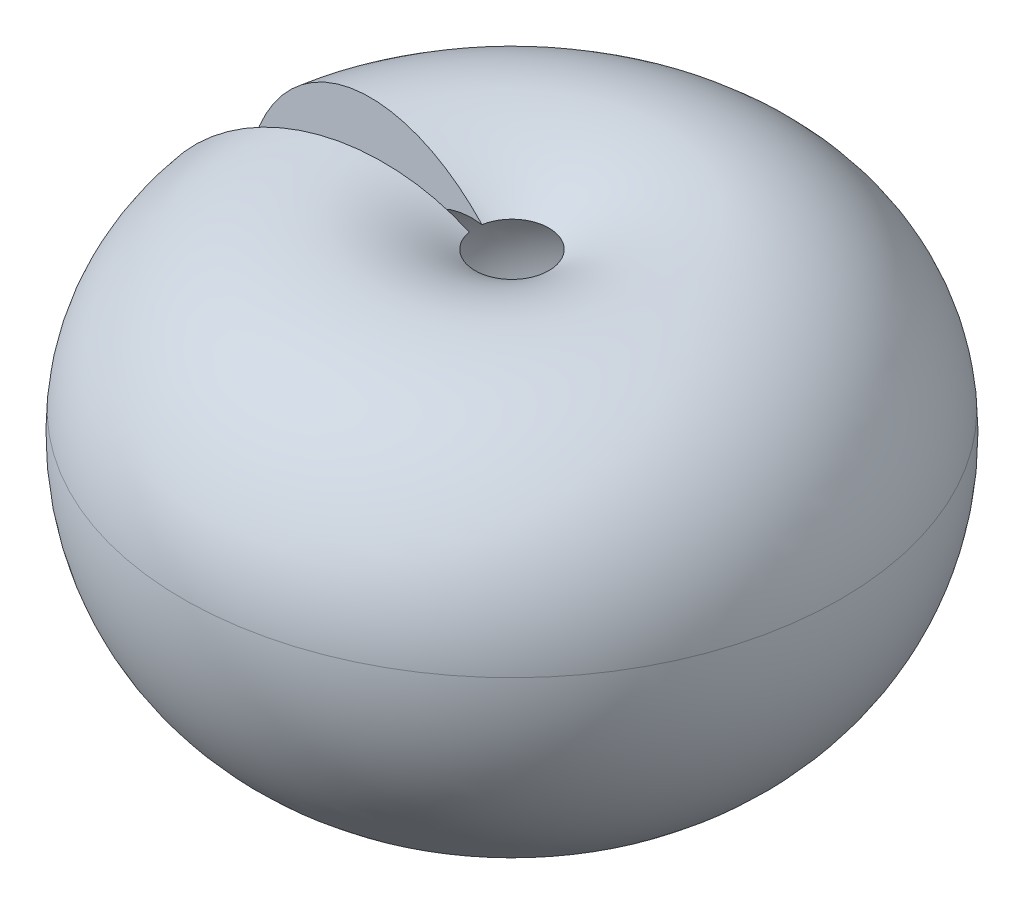
SolidWorks part; units mm, degrees
ref_plane "Front Plane" through (0, 0, 0) normal (0, 0, 1) x (1, 0, 0)
ref_plane "Top Plane" through (0, 0, 0) normal (0, 1, 0) x (1, 0, 0)
ref_plane "Right Plane" through (0, 0, 0) normal (1, 0, 0) x (0, 0, -1)
sketch "Sketch1" plane through (0, 0, 0) normal (0, 0, 1) x (1, 0, 0)
  line L2 (0, 0) -> (0, -2344.0585) construction
  line L4 (0, -1511.6455) -> (0, -1961.8567)
  arc A6 (184.4131, 96.9435) -> (1641.3807, -595.0477) centre (713.8156, -668.2121) cw
  arc A7 (1641.3807, -595.0477) -> (183.5792, -1990.5035) centre (342.6517, -697.4887) cw
  arc A8 (-680.671, -1742.1928) -> (183.5792, -1990.5035) centre (533.8794, 856.8984) ccw
  arc A9 (-1186.6568, -1197.8502) -> (-680.671, -1742.1928) centre (-261.5317, -845.2507) ccw
  arc A10 (-1186.6568, -1197.8502) -> (500.802, -900.7887) centre (-410.7234, -664.2039) ccw
  arc A11 (500.802, -900.7887) -> (184.4131, 96.9435) centre (150, -463) ccw
  point P14 (208, -1792)
  point P15 (-596, -1561)
  point P22 (108.993, 38.838)
revolve "Revolve4" add sketch "Sketch1" angle 170 about L2
